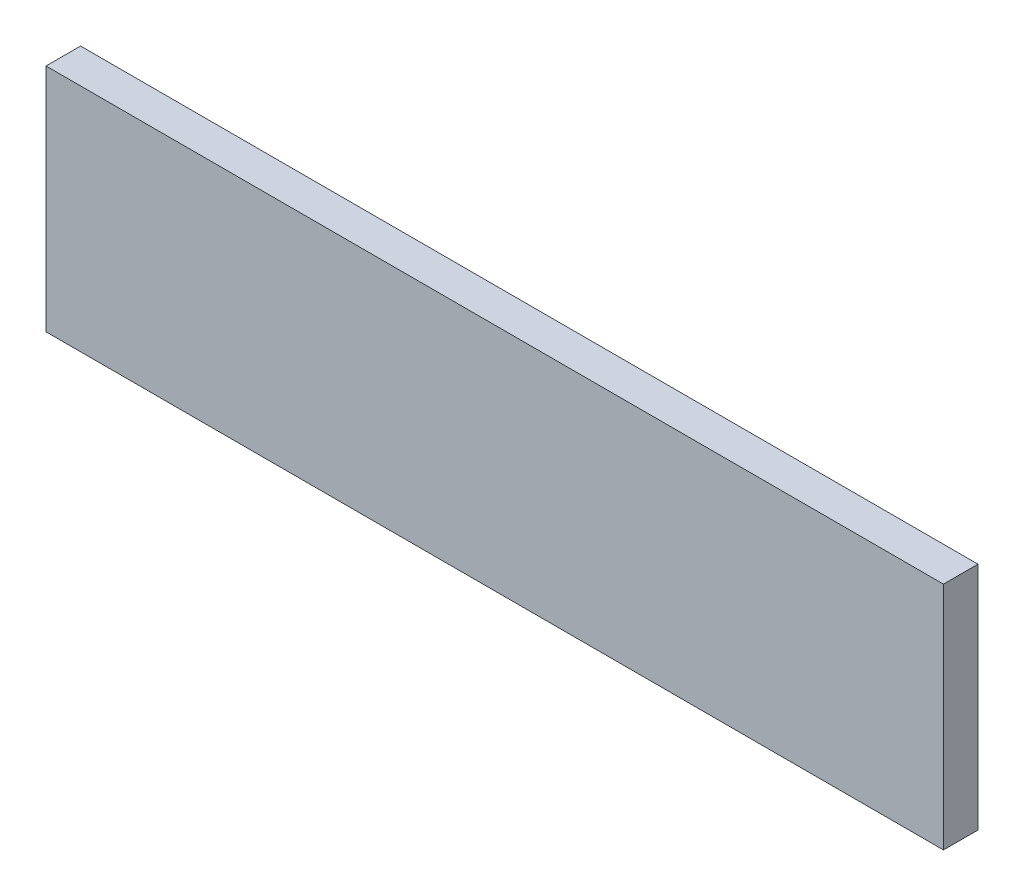
SolidWorks part; units mm, degrees
material "Beech"
ref_plane "Front Plane" through (0, 0, 0) normal (0, 0, 1) x (1, 0, 0)
ref_plane "Top Plane" through (0, 0, 0) normal (0, 1, 0) x (1, 0, 0)
ref_plane "Right Plane" through (0, 0, 0) normal (1, 0, 0) x (0, 0, -1)
sketch "Sketch1" plane through (0, 0, 0) normal (0, 0, 1) x (1, 0, 0)
  line L0 (-157.3266, 4967.6971) -> (-157.3266, 5284.8315) construction
  line L5 (-157.3266, 5411.8315) -> (337.7194, 5411.8315)
  line L6 (-157.3266, 5411.8315) -> (-157.3266, 5284.8315)
  line L7 (-157.3266, 5284.8315) -> (337.7194, 5284.8315)
  line L9 (90.1964, 5267.1362) -> (90.1964, 5460.8032) construction
  line L10 (26.6964, 5267.1362) -> (153.6964, 5267.1362) construction
  line L11 (-176.3766, 5460.8032) -> (356.7694, 5460.8032) construction
  line L12 (-157.3266, 5348.3315) -> (90.1964, 5348.3315) construction
  line L13 (337.7194, 5411.8315) -> (337.7194, 5284.8315)
  point P12 (-76.4911, 5348.3315)
  point P17 (90.1964, 5411.8315)
  point P18 (90.1964, 5284.8315)
  dimension "D1" = 127
extrude "Boss-Extrude1" add sketch "Sketch1" along normal blind 19.05
